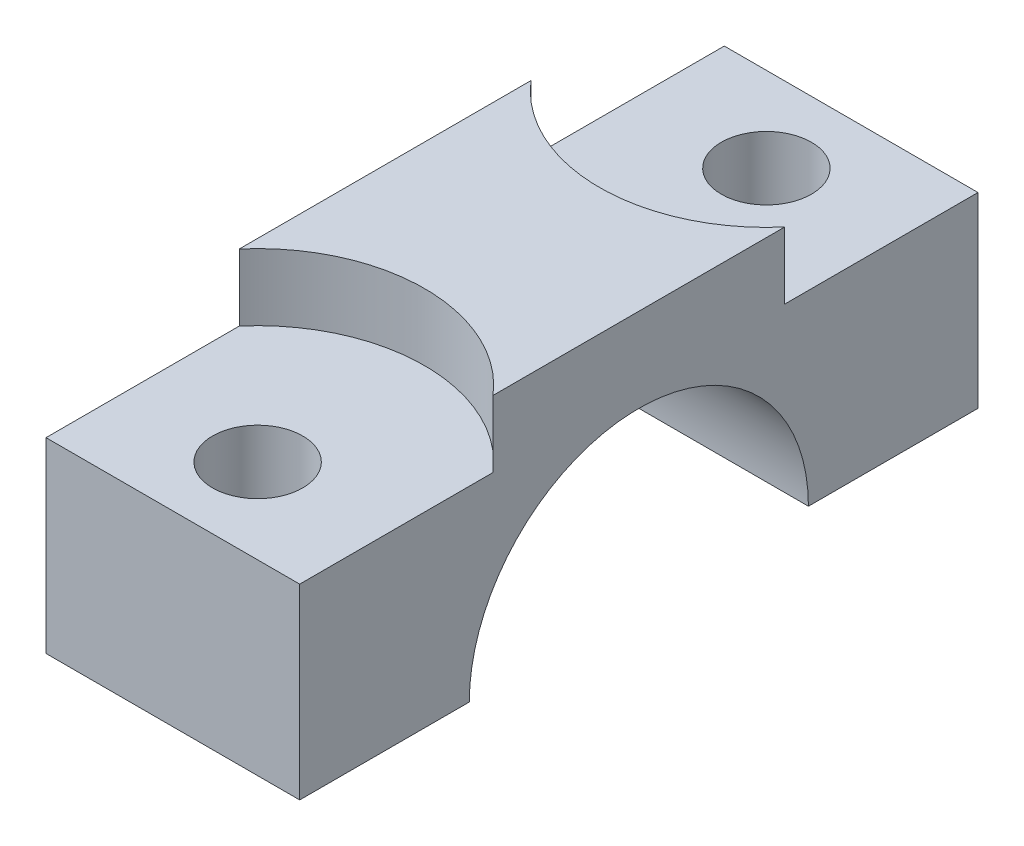
SolidWorks part; units mm, degrees
ref_plane "Front Plane" through (0, 0, 0) normal (0, 0, 1) x (1, 0, 0)
ref_plane "Top Plane" through (0, 0, 0) normal (0, 1, 0) x (1, 0, 0)
ref_plane "Right Plane" through (0, 0, 0) normal (1, 0, 0) x (0, 0, -1)
sketch "Sketch1" plane through (0, 0, 0) normal (1, 0, 0) x (0, 0, -1)
  line L1 (-25.4, 19) -> (25.4, 19)
  line L2 (-25.4, 19) -> (-25.4, 0)
  line L3 (-25.4, 0) -> (25.4, 0)
  line L4 (25.4, 19) -> (25.4, 0)
  line L5 (-25.4, 19) -> (25.4, 0) construction
  line L6 (-25.4, 0) -> (25.4, 19) construction
  circle A0 centre (0, 0) radius 12.7
  point P0 (0, 9.5)
  dimension "D1" = 25.4
  dimension "D2" = 50.8
  dimension "D3" = 19
extrude "Boss-Extrude1" add sketch "Sketch1" along normal mid plane 19 contours A0 L3 L4 L1 L2
sketch "Sketch2" plane through (0, 0, 0) normal (0, -1, 0) x (1, 0, 0)
  line L0 (0, 25.4) -> (0, 12.7) construction
  line L1 (9.5, 25.4) -> (-9.5, 25.4) construction
  line L2 (9.5, 12.7) -> (-9.5, 12.7) construction
  line L3 (0, -12.7) -> (0, -25.4) construction
  line L4 (9.5, -12.7) -> (-9.5, -12.7) construction
  line L5 (9.5, -25.4) -> (-9.5, -25.4) construction
  point P12 (0, 19.05)
  point P13 (0, -19.05)
hole_wizard "CBORE for M12 Hex Head Cap Screw1" positions "Sketch5" profile "Sketch6" counterbore size "M12" standard "ISO" end condition through all
sketch "Sketch5" plane through (0, 19, 0) normal (0, 1, 0) x (1, 0, 0)
  point P0 (0, 19.05)
  point P3 (0, -19.05)
sketch "Sketch6" plane through (0, 19, -19.05) normal (1, 0, 0) x (0, 0, 1)
  line L0 (0, 0) -> (0, 19)
  line L1 (0, 19) -> (3.375, 19)
  line L3 (3.375, 19) -> (3.375, 5)
  line L4 (3.375, 5) -> (12.5, 5)
  line L5 (12.5, 5) -> (12.5, 0)
  line L7 (12.5, 0) -> (0, 0)
  line L11 (0, -6.35) -> (0, 107.95) construction
  dimension "Thru Hole Dia." = 6.75
  dimension "Thru Hole Depth" = 19
  dimension "C'Bore Dia." = 25
  dimension "C'Bore Depth" = 5
